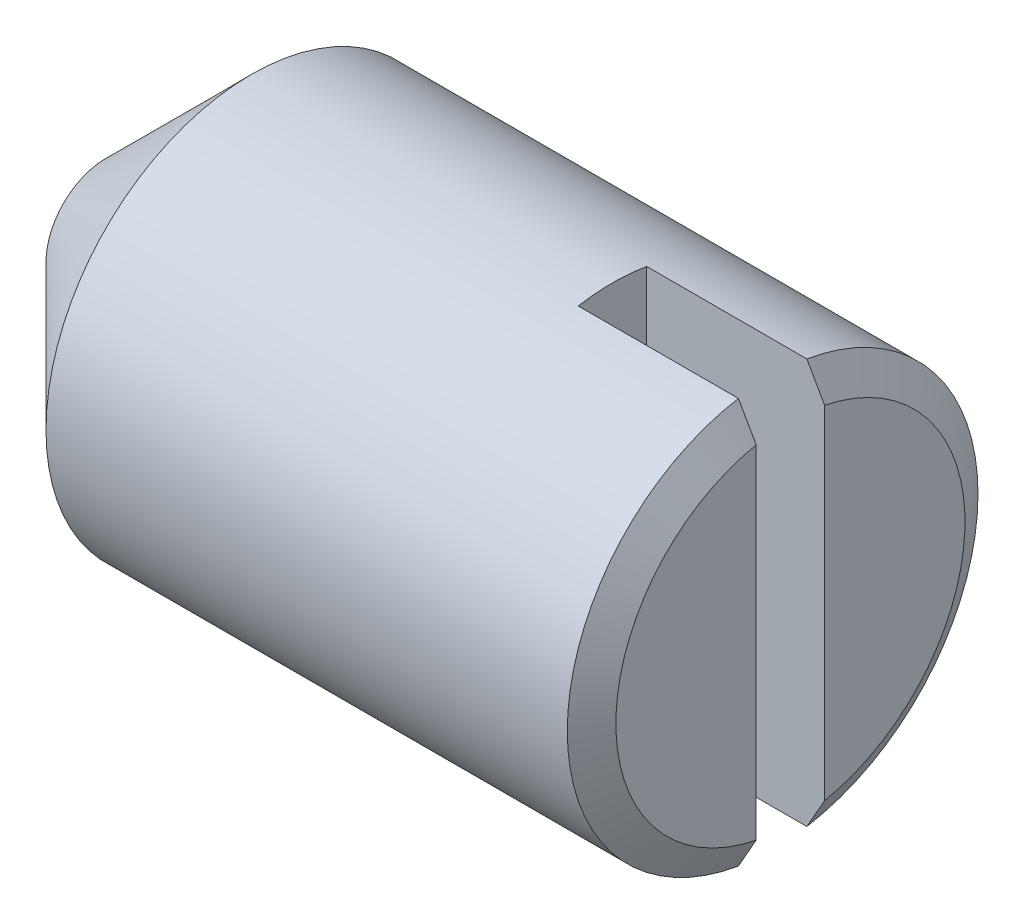
SolidWorks part; units mm, degrees
ref_plane "Přední rovina" through (0, 0, 0) normal (0, 0, 1) x (1, 0, 0)
ref_plane "Vrchní rovina" through (0, 0, 0) normal (0, 1, 0) x (1, 0, 0)
ref_plane "Pravá rovina" through (0, 0, 0) normal (1, 0, 0) x (0, 0, -1)
sketch "Skica1" plane through (0, 0, 0) normal (0, 1, 0) x (1, 0, 0)
  line L0 (0, 0) -> (0, 0.175)
  line L1 (0, 0.175) -> (0.425, 0.6)
  line L2 (0.425, 0.6) -> (1.948, 0.6)
  line L3 (1.948, 0.6) -> (2, 0.51)
  line L4 (2, 0.51) -> (2, 0)
  line L5 (2, 0) -> (0, 0) construction
  line L6 (0, 0) -> (2, 0)
  dimension "D1" = 45
  dimension "l" = 2
  dimension "M" = 1.2
  dimension "D4" = 1.02
  dimension "ALFA/2" = 60
  dimension "dp" = 0.35
revolve "Otočit kolem osy1" add sketch "Skica1" angle 360 about L5
cosmetic thread "Kosmetický závit1" parameters "D2"=0.9
sketch "Skica2" plane through (2, 0, 0) normal (1, 0, 0) x (0, 0, -1)
  line L0 (0, 0.6) -> (0, 0) construction
  line L1 (-0.1, 0.6) -> (0.1, 0.6)
  line L2 (-0.1, 0.6) -> (-0.1, -0.6)
  line L3 (-0.1, -0.6) -> (0.1, -0.6)
  line L4 (0.1, 0.6) -> (0.1, -0.6)
  line L5 (0, 0) -> (0.1, 0) construction
  circle A0 centre (0, 0) radius 0.6 construction
  dimension "n" = 0.2
extrude "Odebrat vysunutím1" cut sketch "Skica2" against normal blind 0.52
equation "\"D4@Skica1\" = \"M@Skica1\" * 0.85"
